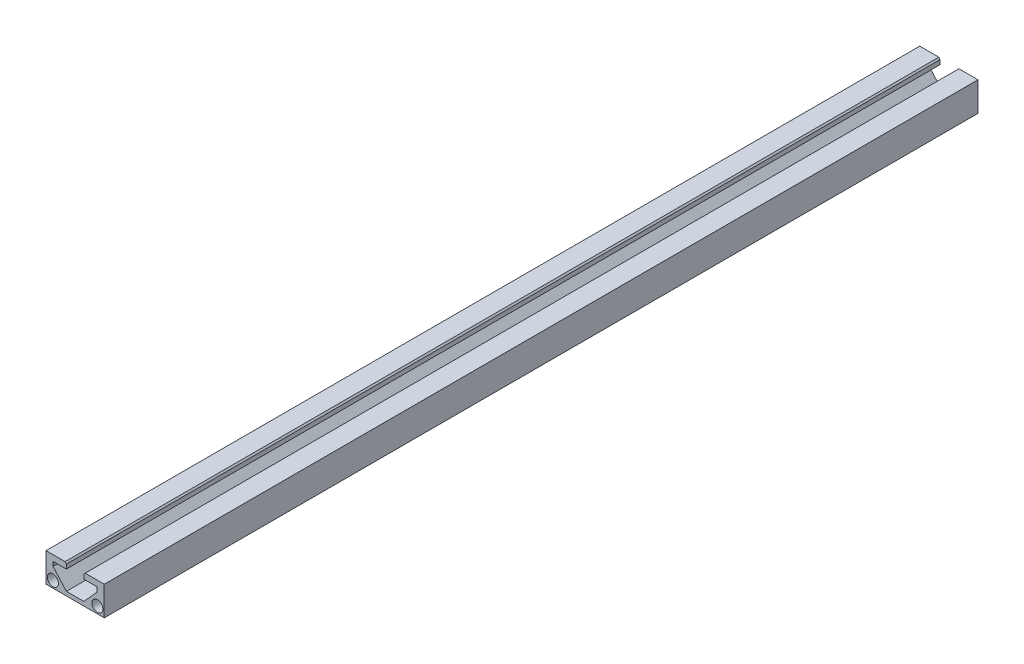
SolidWorks part; units mm, degrees
ref_plane "Front Plane" through (0, 0, 0) normal (0, 0, 1) x (1, 0, 0)
ref_plane "Top Plane" through (0, 0, 0) normal (0, 1, 0) x (1, 0, 0)
ref_plane "Right Plane" through (0, 0, 0) normal (1, 0, 0) x (0, 0, -1)
sketch "Sketch1" plane through (0, 0, 0) normal (0, 0, 1) x (1, 0, 0)
  line L0 (0, 0) -> (0, -1.383)
  line L1 (0, -1.383) -> (10, -1.383)
  line L2 (10, -1.383) -> (10, 8.617)
  line L3 (10, 8.617) -> (3.4482, 8.617)
  line L4 (3.4482, 8.617) -> (3, 8.117)
  line L5 (3, 8.117) -> (3, 6.617)
  line L6 (3, 6.617) -> (7.587, 6.617)
  line L7 (7.587, 6.617) -> (7.587, 5.117)
  line L8 (7.587, 5.117) -> (3, 0)
  line L9 (3, 0) -> (0, 0)
  dimension "D1" = 10
  dimension "D2" = 10
  dimension "D3" = 3
  dimension "D4" = 1.5
  dimension "D5" = 3
  dimension "D6" = 2
  dimension "D7" = 1.5
extrude "Boss-Extrude1" add sketch "Sketch1" along normal mid plane 300
mirror "Mirror1" about plane through (0, 0, 0) normal (1, 0, 0) of "Boss-Extrude1"
sketch "Sketch2" plane through (0, 0, 150) normal (0, 0, 1) x (1, 0, 0)
  line L0 (10, -1.383) -> (5.6551, 2.9619) construction
  line L1 (7.587, 5.117) -> (3, 0) construction
  circle A0 centre (7.6467, 0.9703) radius 1.9
  dimension "D1" = 3.8
extrude "Cut-Extrude1" cut sketch "Sketch2" against normal through all
mirror "Mirror2" about plane through (0, 0, 0) normal (1, 0, 0) of "Cut-Extrude1"
sketch "Sketch3" plane through (0, 0, 0) normal (0, 1, 0) x (1, 0, 0)
  line L0 (3, -150) -> (-3, -150) construction
  circle A0 centre (0, -140) radius 2
  point P4 (0, -150)
  dimension "D2" = 4
  dimension "D1" = 10
extrude "Cut-Extrude2" cut sketch "Sketch3" against normal blind 10
mirror "Mirror3" about plane through (0, 0, 0) normal (0, 0, 1) of "Cut-Extrude2"
